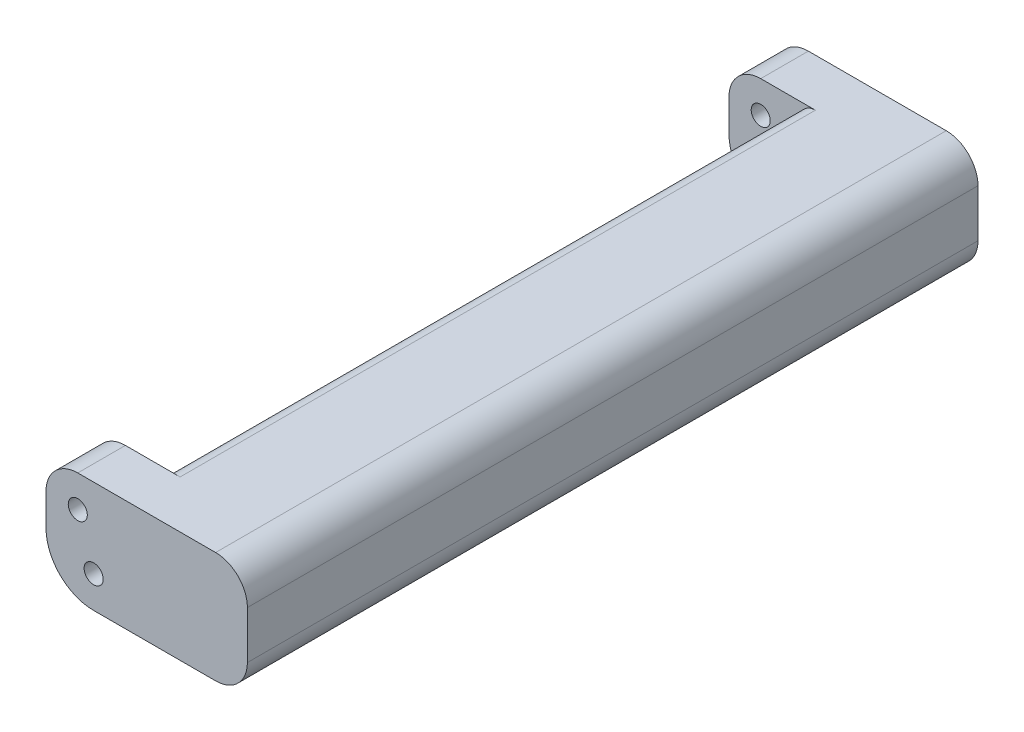
SolidWorks part; units mm, degrees
ref_plane "Front Plane" through (0, 0, 0) normal (0, 0, 1) x (1, 0, 0)
ref_plane "Top Plane" through (0, 0, 0) normal (0, 1, 0) x (1, 0, 0)
ref_plane "Right Plane" through (0, 0, 0) normal (1, 0, 0) x (0, 0, -1)
sketch "Sketch1" plane through (0, 0, 0) normal (0, 0, 1) x (1, 0, 0)
  line L0 (-31.75, 25.4) -> (-31.75, 0)
  line L1 (-38.1, 25.4) -> (25.4, 25.4)
  line L2 (-38.1, 25.4) -> (-38.1, 0)
  line L3 (-38.1, 0) -> (25.4, 0)
  line L4 (25.4, 25.4) -> (25.4, 0)
  line L5 (8.509, 25.4) -> (8.509, 0)
  circle A0 centre (-25.4, 19.05) radius 1.905
  circle A1 centre (-22.225, 9.525) radius 1.905
  circle A2 centre (15.875, 15.875) radius 6.858
  dimension "D5" = 3.81
  dimension "D6" = 3.81
  dimension "D13" = 13.716
  dimension "D1" = 25.4
  dimension "D2" = 0
  dimension "D3" = 25.4
  dimension "D4" = 38.1
  dimension "D7" = 6.35
  dimension "D8" = 12.7
  dimension "D9" = 15.875
  dimension "D10" = 9.525
  dimension "D11" = 6.35
  dimension "D12" = 30.734
  dimension "D14" = 9.525
  dimension "D15" = 9.525
extrude "Boss-Extrude1" add sketch "Sketch1" along normal blind 9.525
sketch "Sketch2" plane through (0, 0, 9.525) normal (0, 0, 1) x (1, 0, 0)
  line L0 (-19.05, 25.4) -> (-9.525, 0)
  line L1 (-31.75, 25.4) -> (8.509, 25.4) construction
  line L2 (-31.75, 0) -> (8.509, 0) construction
  line L3 (-19.05, 25.4) -> (8.509, 25.4)
  line L4 (8.509, 25.4) -> (8.509, 0)
  line L5 (8.509, 0) -> (-9.525, 0)
  circle A0 centre (-25.4, 19.05) radius 1.905 construction
  dimension "D2" = 15.875
  dimension "D1" = 6.35
extrude "Boss-Extrude2" add sketch "Sketch2" along normal blind 127
sketch "Sketch3" plane through (0, 0, 136.525) normal (0, 0, 1) x (1, 0, 0)
  line L0 (8.509, 25.4) -> (-19.05, 25.4) construction
  line L2 (-9.525, 0) -> (8.509, 0) construction
  line L3 (8.509, 0) -> (8.509, 25.4) construction
  line L5 (-19.05, 25.4) -> (-31.75, 25.4) construction
  line L6 (-31.75, 25.4) -> (-31.75, 0) construction
  line L7 (-31.75, 0) -> (-9.525, 0) construction
  line L8 (8.509, 25.4) -> (-19.05, 25.4)
  line L10 (-9.525, 0) -> (8.509, 0)
  line L11 (8.509, 0) -> (8.509, 25.4)
  line L13 (-19.05, 25.4) -> (-31.75, 25.4)
  line L14 (-31.75, 25.4) -> (-31.75, 0)
  line L15 (-31.75, 0) -> (-9.525, 0)
  circle A0 centre (-25.4, 19.05) radius 1.905 construction
  circle A1 centre (-25.4, 19.05) radius 1.905
  circle A2 centre (-22.225, 9.525) radius 1.905 construction
  circle A3 centre (-22.225, 9.525) radius 1.905
extrude "Boss-Extrude3" add sketch "Sketch3" along normal blind 9.525
fillet "Fillet2" radius 6.35 3 edges at (8.509, 25.4, 73.025) (-31.75, 25.4, 141.2875) (-31.75, 25.4, 4.7625)
fillet "Fillet3" radius 3.175 1 edges at (-19.05, 25.4, 73.025)
sketch "Sketch4" plane through (0, 0, 146.05) normal (0, 0, 1) x (1, 0, 0)
  line L0 (8.509, 3.175) -> (-40.1503, 3.175)
  line L4 (8.509, 0) -> (8.509, 19.05)
  line L5 (2.159, 25.4) -> (-25.4, 25.4)
  line L6 (-31.75, 19.05) -> (-31.75, 0)
  line L7 (-31.75, 0) -> (8.509, 0)
  line L8 (8.509, 0) -> (8.509, 19.05)
  line L9 (2.159, 25.4) -> (-25.4, 25.4)
  line L10 (-31.75, 19.05) -> (-31.75, 0)
  line L11 (-31.75, 0) -> (8.509, 0)
  arc A3 (8.509, 19.05) -> (2.159, 25.4) centre (2.159, 19.05) ccw
  arc A4 (-25.4, 25.4) -> (-31.75, 19.05) centre (-25.4, 19.05) ccw
  arc A6 (8.509, 19.05) -> (2.159, 25.4) centre (2.159, 19.05) ccw
  arc A7 (-25.4, 25.4) -> (-31.75, 19.05) centre (-25.4, 19.05) ccw
  dimension "D2" = 3.175
  dimension "D1" = 0
extrude "Cut-Extrude1" cut sketch "Sketch4" against normal up to surface (146.05 mm away)
fillet "Fillet4" radius 9.525 2 edges at (-31.75, 3.175, 4.7625) (-31.75, 3.175, 141.2875)
fillet "Fillet6" radius 6.35 1 edges at (8.509, 3.175, 73.025)
